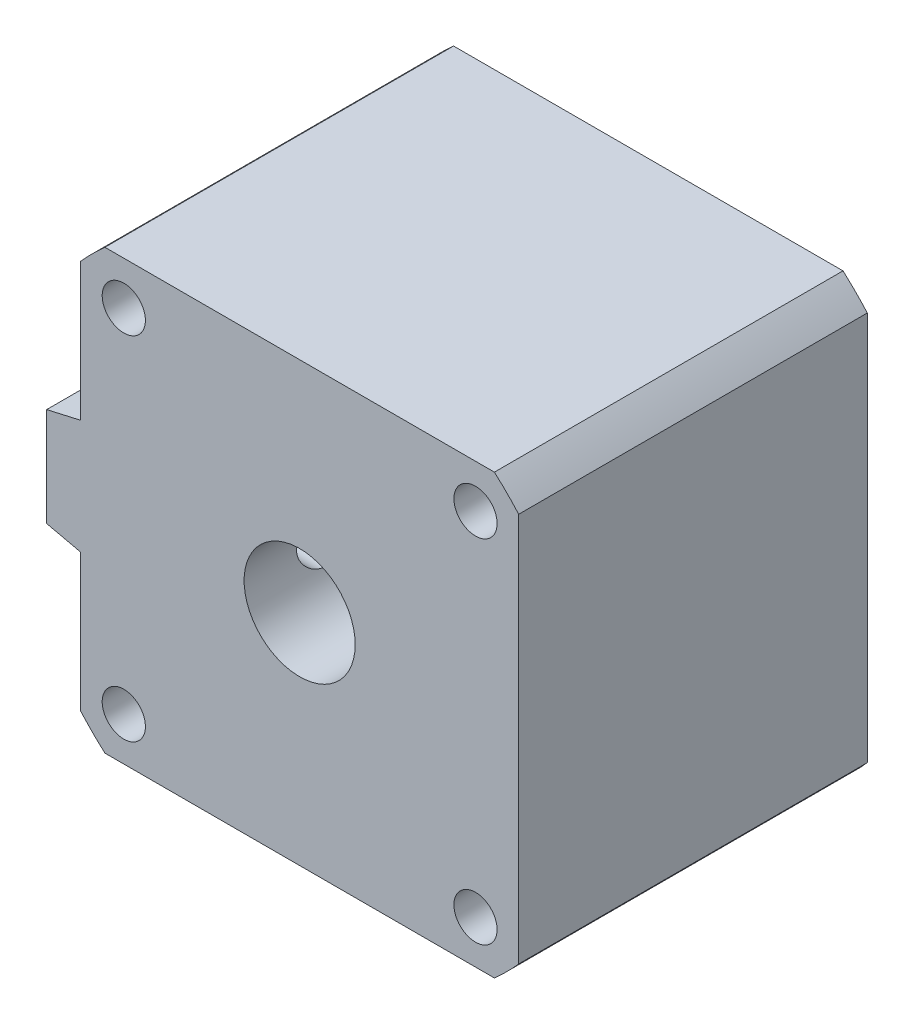
SolidWorks part; units mm, degrees
ref_plane "前视基准面" through (0, 0, 0) normal (0, 0, 1) x (1, 0, 0)
ref_plane "上视基准面" through (0, 0, 0) normal (0, 1, 0) x (1, 0, 0)
ref_plane "右视基准面" through (0, 0, 0) normal (1, 0, 0) x (0, 0, -1)
sketch "草图1" plane through (0, 0, 0) normal (0, 0, 1) x (1, 0, 0)
  line L1 (0, 0) -> (142, 0)
  line L2 (0, 0) -> (0, -142)
  line L3 (0, -142) -> (142, -142)
  line L4 (142, 0) -> (142, -142)
  dimension "D1" = 142
  dimension "D2" = 142
extrude "拉伸1" add sketch "草图1" along normal blind 113
sketch "草图2" plane through (0, 0, 113) normal (0, 0, 1) x (1, 0, 0)
  circle A0 centre (14, -14) radius 7
  circle A1 centre (128, -14) radius 7
  circle A2 centre (14, -128) radius 7
  circle A3 centre (128, -128) radius 7
extrude "切除-拉伸1" cut sketch "草图2" against normal blind 113
sketch "草图3" plane through (0, 0, 113) normal (0, 0, 1) x (1, 0, 0)
  circle A0 centre (71, -71) radius 18
extrude "切除-拉伸2" cut sketch "草图3" against normal blind 103
sketch "草图4" plane through (0, 0, 0) normal (0, 0, -1) x (-1, 0, 0)
  circle A0 centre (-71, -71) radius 95
extrude "切除-拉伸3" cut sketch "草图4" against normal through all flip side to cut
sketch "草图5" plane through (0, 0, 0) normal (0, 0, -1) x (-1, 0, 0)
  line L0 (11, -55) -> (0, -52.5)
  line L2 (0, -52.5) -> (0, -55)
  line L4 (0, -55) -> (0, -87)
  line L5 (0, -89.5) -> (0, -87)
  line L6 (0, -7.8811) -> (0, -134.1189) construction
  line L7 (11, -7.8811) -> (11, -134.1189)
  line L8 (11, -55) -> (11, -87)
  line L9 (11, -87) -> (0, -89.5)
  dimension "D4" = 11
extrude "拉伸2" add sketch "草图5" against normal blind 113
sketch "草图6" plane through (-11, 0, 0) normal (-1, 0, 0) x (0, 0, 1)
  circle A0 centre (24.5, -71) radius 7.5
  circle A1 centre (88.5, -71) radius 7.5
extrude "切除-拉伸4" cut sketch "草图6" against normal blind 113
